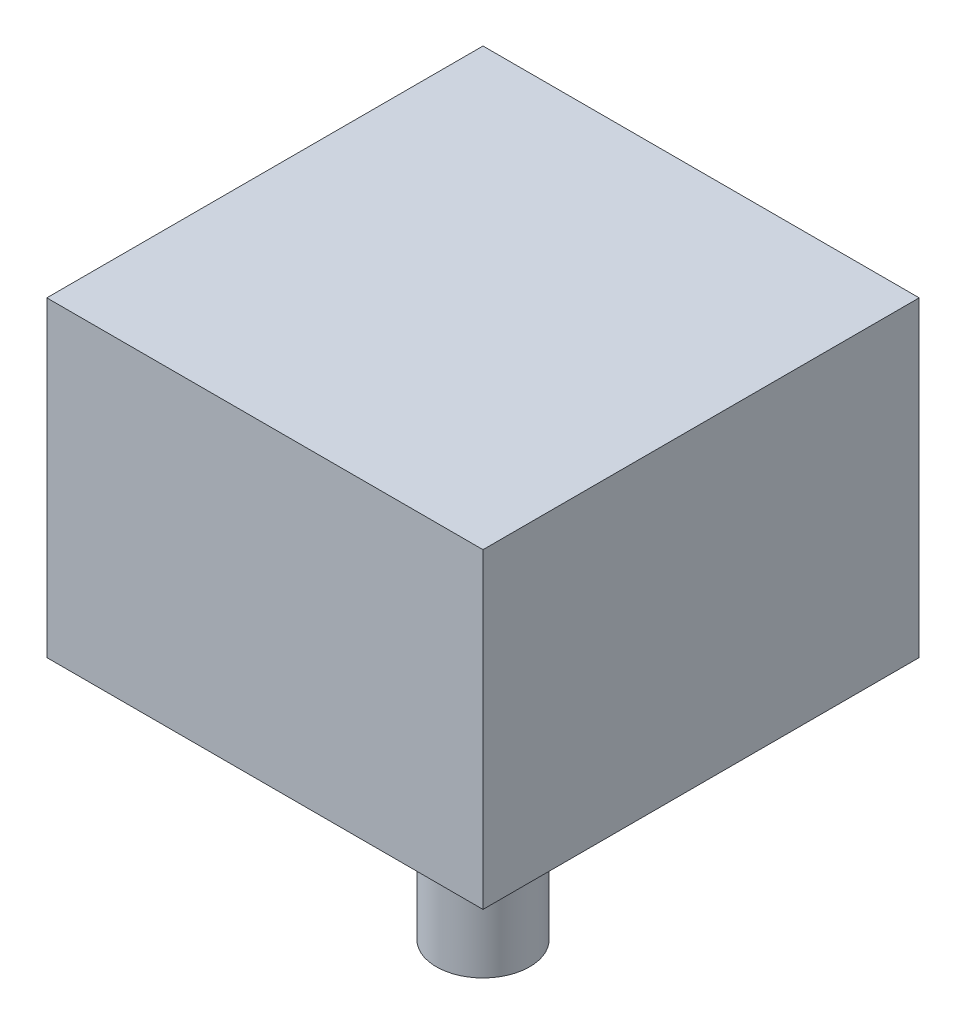
SolidWorks part; units mm, degrees
ref_plane "Front Plane" through (0, 0, 0) normal (0, 0, 1) x (1, 0, 0)
ref_plane "Top Plane" through (0, 0, 0) normal (0, 1, 0) x (1, 0, 0)
ref_plane "Right Plane" through (0, 0, 0) normal (1, 0, 0) x (0, 0, -1)
sketch "Sketch1" plane through (0, 0, 0) normal (0, 1, 0) x (1, 0, 0)
  line L1 (-14, 14) -> (14, 14)
  line L2 (-14, 14) -> (-14, -14)
  line L3 (-14, -14) -> (14, -14)
  line L4 (14, 14) -> (14, -14)
  line L5 (-14, 14) -> (14, -14) construction
  line L6 (-14, -14) -> (14, 14) construction
  point P0 (0, 0)
  dimension "D1" = 28
  dimension "D2" = 28
extrude "Boss-Extrude1" add sketch "Sketch1" against normal mid plane 20 contours L1 L4 L3 L2
sketch "Sketch2" plane through (0, 0, 0) normal (0, 0, 1) x (1, 0, 0)
  line L0 (0, -15) -> (0, -1)
  line L1 (0, -11) -> (0, 11) construction
  line L2 (-14, -10) -> (14, -10) construction
  arc A0 (0, -15) -> (0, -1) centre (0, -8) ccw
  dimension "D1" = 7
  dimension "D2" = 5
revolve "Cut-Revolve1" cut sketch "Sketch2" angle 360 about L0
sketch "Sketch3" plane through (0, 0, 0) normal (0, 0, 1) x (1, 0, 0)
  line L0 (0, -15) -> (0, -1) construction
  line L1 (0, -1) -> (0, -14.4)
  line L4 (0, -14.4) -> (0, -25.6908)
  line L5 (0, -25.6908) -> (3, -25.6908)
  line L6 (3, -13.6908) -> (3, -25.6908)
  arc A0 (3, -13.6908) -> (0, -1) centre (0, -7.7) ccw
  arc A1 (0, -15) -> (0, -1) centre (0, -8) ccw construction
  point P1 (0, 0)
  point P2 (0, 0)
  point P3 (0, -0.8685)
  point P13 (0, -1.529)
  dimension "D1" = 0.6
  dimension "D2" = 3
  dimension "D3" = 12
revolve "Revolve1" add sketch "Sketch3" angle 360 about L0
sketch "Sketch4" plane through (0, 0, 14) normal (0, 0, 1) x (1, 0, 0)
  line L0 (3, -13.6908) -> (-3, -13.6908) construction
  circle A0 centre (0, -17.6908) radius 1.55
  point P4 (0, 0)
  dimension "D1" = 3.1
  dimension "D2" = 4
extrude "Cut-Extrude1" cut sketch "Sketch4" against normal through all both and the other way through all contours A0
